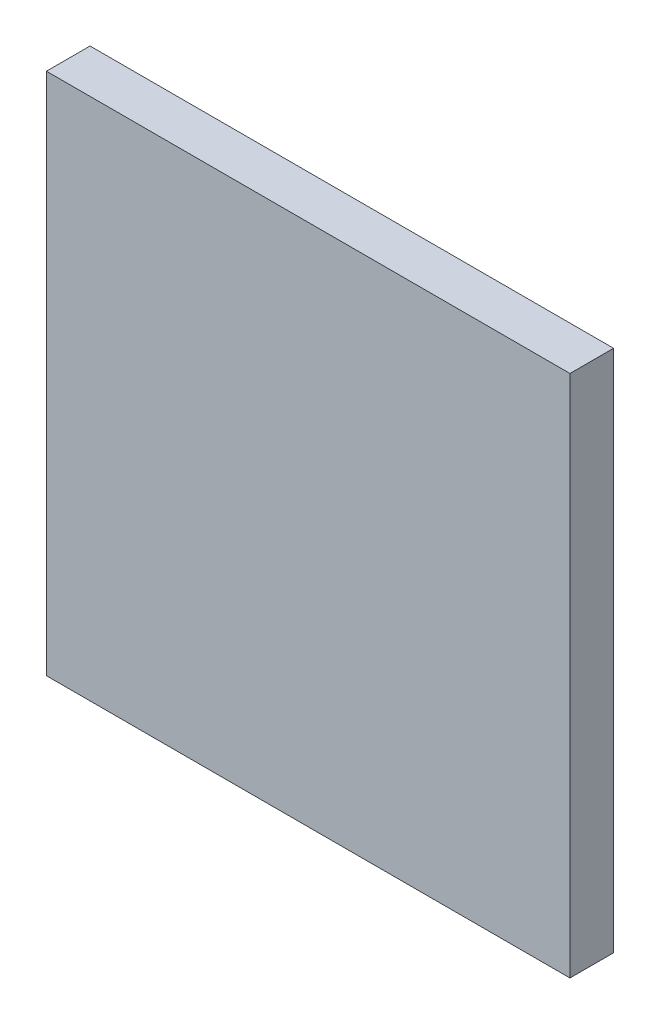
SolidWorks part; units mm, degrees
ref_plane "Front Plane" through (0, 0, 0) normal (0, 0, 1) x (1, 0, 0)
ref_plane "Top Plane" through (0, 0, 0) normal (0, 1, 0) x (1, 0, 0)
ref_plane "Right Plane" through (0, 0, 0) normal (1, 0, 0) x (0, 0, -1)
sketch "Sketch1" plane through (0, 0, 0) normal (0, 0, 1) x (1, 0, 0)
  line L1 (76.2, 76.2) -> (-76.2, 76.2)
  line L2 (76.2, 76.2) -> (76.2, -76.2)
  line L3 (76.2, -76.2) -> (-76.2, -76.2)
  line L4 (-76.2, 76.2) -> (-76.2, -76.2)
  line L5 (76.2, 76.2) -> (-76.2, -76.2) construction
  line L6 (76.2, -76.2) -> (-76.2, 76.2) construction
  point P0 (0, 0)
  dimension "D1" = 152.4
  dimension "D2" = 152.4
extrude "Boss-Extrude1" add sketch "Sketch1" along normal blind 12.7
